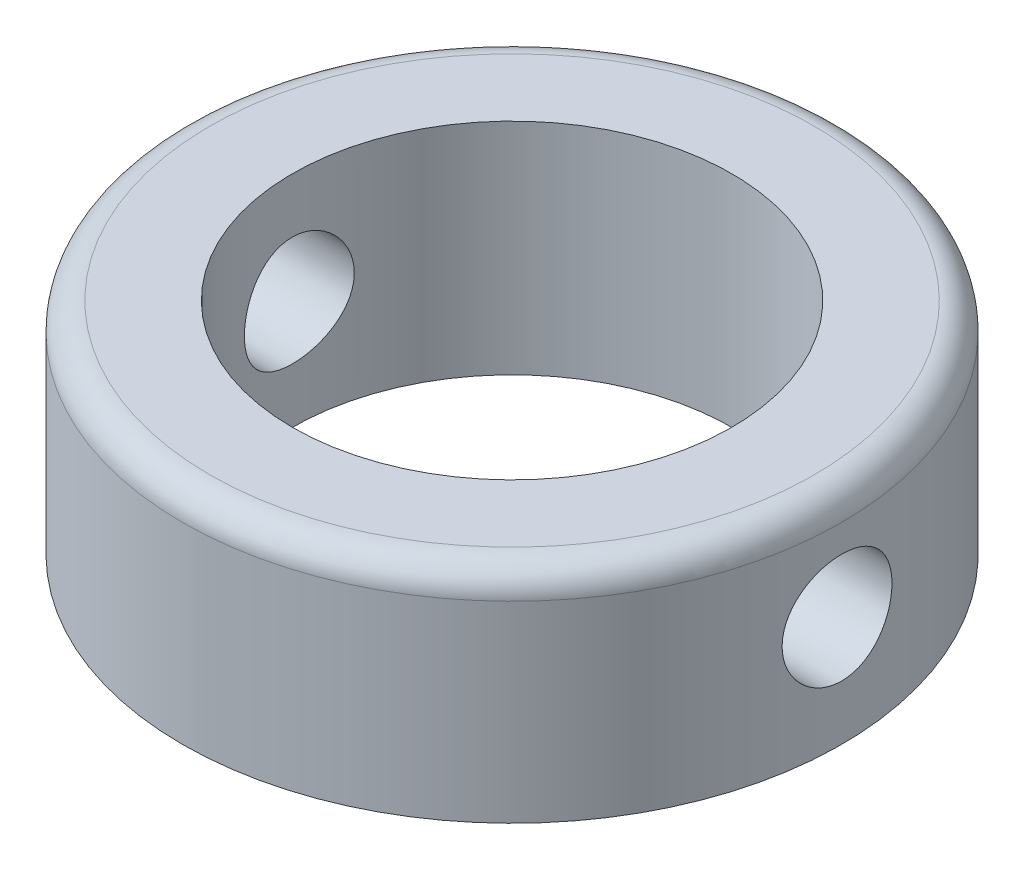
SolidWorks part; units mm, degrees
ref_plane "Front Plane" through (0, 0, 0) normal (0, 0, 1) x (1, 0, 0)
ref_plane "Top Plane" through (0, 0, 0) normal (0, 1, 0) x (1, 0, 0)
ref_plane "Right Plane" through (0, 0, 0) normal (1, 0, 0) x (0, 0, -1)
sketch "Sketch2" plane through (0, 0, 0) normal (0, 1, 0) x (1, 0, 0)
  circle A0 centre (0, 0) radius 8
  circle A1 centre (0, 0) radius 12
  dimension "D1" = 16
  dimension "D2" = 24
extrude "Boss-Extrude1" add sketch "Sketch2" along normal blind 8
fillet "Fillet1" radius 1 1 edges at (0, 8, 12)
sketch "Sketch3" plane through (0, 0, 0) normal (1, 0, 0) x (0, 0, -1)
  circle A0 centre (0, 4) radius 2
  dimension "D1" = 4
  dimension "D2" = 4
extrude "Cut-Extrude1" cut sketch "Sketch3" against normal through all both and the other way through all
